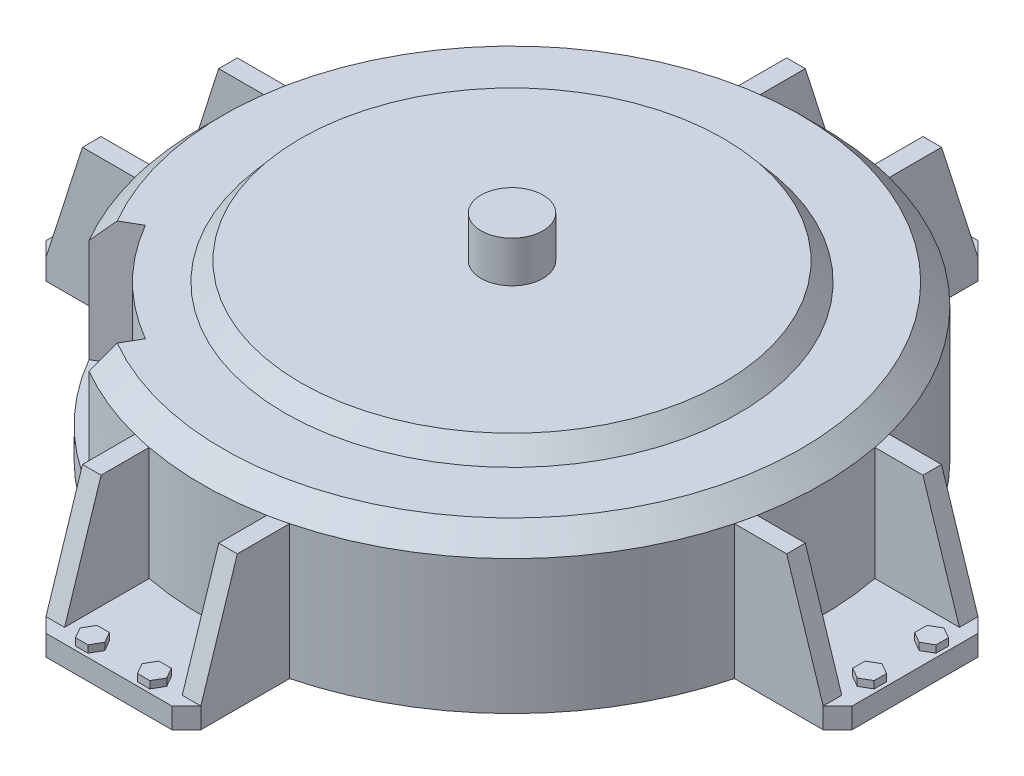
SolidWorks part; units mm, degrees
ref_plane "Front Plane" through (0, 0, 0) normal (0, 0, 1) x (1, 0, 0)
ref_plane "Top Plane" through (0, 0, 0) normal (0, 1, 0) x (1, 0, 0)
ref_plane "Right Plane" through (0, 0, 0) normal (1, 0, 0) x (0, 0, -1)
sketch "Sketch1" plane through (0, 0, 0) normal (0, 1, 0) x (1, 0, 0)
  circle A0 centre (0, 0) radius 150
  dimension "D1" = 300
extrude "Boss-Extrude1" add sketch "Sketch1" along normal blind 75
chamfer "Chamfer1" distance 10 angle 45 1 edges at (0, 75, 150)
sketch "Sketch2" plane through (0, 75, 0) normal (0, 1, 0) x (1, 0, 0)
  line L0 (0, 0) -> (-256.8794, 0) construction
  line L1 (-145.2369, 37.5) -> (-195.2369, 37.5)
  line L2 (-195.2369, 37.5) -> (-195.2369, -37.5)
  line L3 (-195.2369, -37.5) -> (-145.2369, -37.5)
  circle A0 centre (0, 0) radius 150 construction
  arc A1 (-145.2369, 37.5) -> (-145.2369, -37.5) centre (0, 0) ccw
  dimension "D1" = 75
  dimension "D2" = 50
extrude "Boss-Extrude2" add sketch "Sketch2" along normal blind 10 from offset 75 offset against normal yes
chamfer "Chamfer2" distance 7 angle 45 2 edges at (-195.2369, 5, -37.5) (-195.2369, 5, 37.5)
sketch "Sketch3" plane through (0, 0, 37.5) normal (0, 0, 1) x (1, 0, 0)
  line L0 (-145.2369, 10) -> (-145.2369, 65)
  line L1 (-150, 65) -> (150, 65) construction
  line L2 (-145.2369, 65) -> (-170.5569, 65)
  line L3 (-170.5569, 65) -> (-188.2369, 10)
  line L4 (-188.2369, 10) -> (-145.2369, 10)
  dimension "D1" = 17.68
  dimension "D2" = 25.32
extrude "Boss-Extrude3" add sketch "Sketch3" against normal blind 9
sketch "Sketch4" plane through (0, 10, 0) normal (0, 1, 0) x (1, 0, 0)
  line L0 (-150, 0) -> (-204.7628, 0) construction
  line L1 (-188.2369, 37.5) -> (-188.2369, -37.5) construction
  line L3 (-188.2369, -21) -> (-183.0407, -18)
  line L4 (-183.0407, -18) -> (-183.0407, -12)
  line L5 (-183.0407, -12) -> (-188.2369, -9)
  line L6 (-188.2369, -9) -> (-193.433, -12)
  line L7 (-193.433, -12) -> (-193.433, -18)
  line L8 (-193.433, -18) -> (-188.2369, -21)
  arc A0 (-145.2369, -37.5) -> (-147.2676, -28.5) centre (0, 0) ccw construction
  arc A1 (-145.2369, 37.5) -> (-147.2676, -28.5) centre (0, 0) ccw construction
  circle A2 centre (-188.2369, -15) radius 5.1962 construction
  dimension "D1" = 6
  dimension "D2" = 13.5
extrude "Boss-Extrude4" add sketch "Sketch4" along normal blind 3.5
mirror "Mirror1" about plane through (0, 0, 0) normal (0, 0, 1) of "Boss-Extrude3", "Boss-Extrude4"
pattern_circular "CirPattern1" count 4 over 360 about axis through (0, 0, 0) along (0, 1, 0) of "Boss-Extrude4", "Boss-Extrude3", "Mirror1", "Boss-Extrude2", "Chamfer2"
sketch "Sketch5" plane through (0, 75, 0) normal (0, 1, 0) x (1, 0, 0)
  line L0 (0, 169.4585) -> (0, -162.311) construction
  line L1 (253.3737, 0) -> (-282.3192, 0) construction
  line L2 (-112.5833, -65) -> (-121.2436, -70)
  line L3 (-65, -112.5833) -> (-70, -121.2436)
  line L4 (-121.2436, -70) -> (-129.9038, -75)
  line L5 (-70, -121.2436) -> (-75, -129.9038)
  arc A0 (-112.5833, -65) -> (-65, -112.5833) centre (0, 0) ccw
  circle A1 centre (0, 0) radius 140 construction
  circle A2 centre (0, 0) radius 140
  arc A3 (0, -130) -> (-130, 0) centre (0, 0) ccw
  arc A4 (-145.2369, -37.5) -> (-37.5, -145.2369) centre (0, 0) ccw construction
  arc A5 (-145.2369, -37.5) -> (-37.5, -145.2369) centre (0, 0) ccw
  circle M6 centre (0, 0) radius 140
  dimension "D1" = 260
  dimension "D2" = 30
  dimension "D3" = 30
extrude "Cut-Extrude1" cut sketch "Sketch5" against normal blind 60 contours L4 A5 L5 M6 | A0 L2 L3 M6
sketch "Sketch6" plane through (0, 75, 0) normal (0, 1, 0) x (1, 0, 0)
  circle A0 centre (0, 0) radius 110
  dimension "D1" = 220
extrude "Boss-Extrude5" add sketch "Sketch6" along normal blind 9 draft 40
sketch "Sketch7" plane through (0, 84, 0) normal (0, 1, 0) x (1, 0, 0)
  circle A0 centre (0, 0) radius 15
  dimension "D1" = 30
extrude "Boss-Extrude6" add sketch "Sketch7" along normal blind 20
